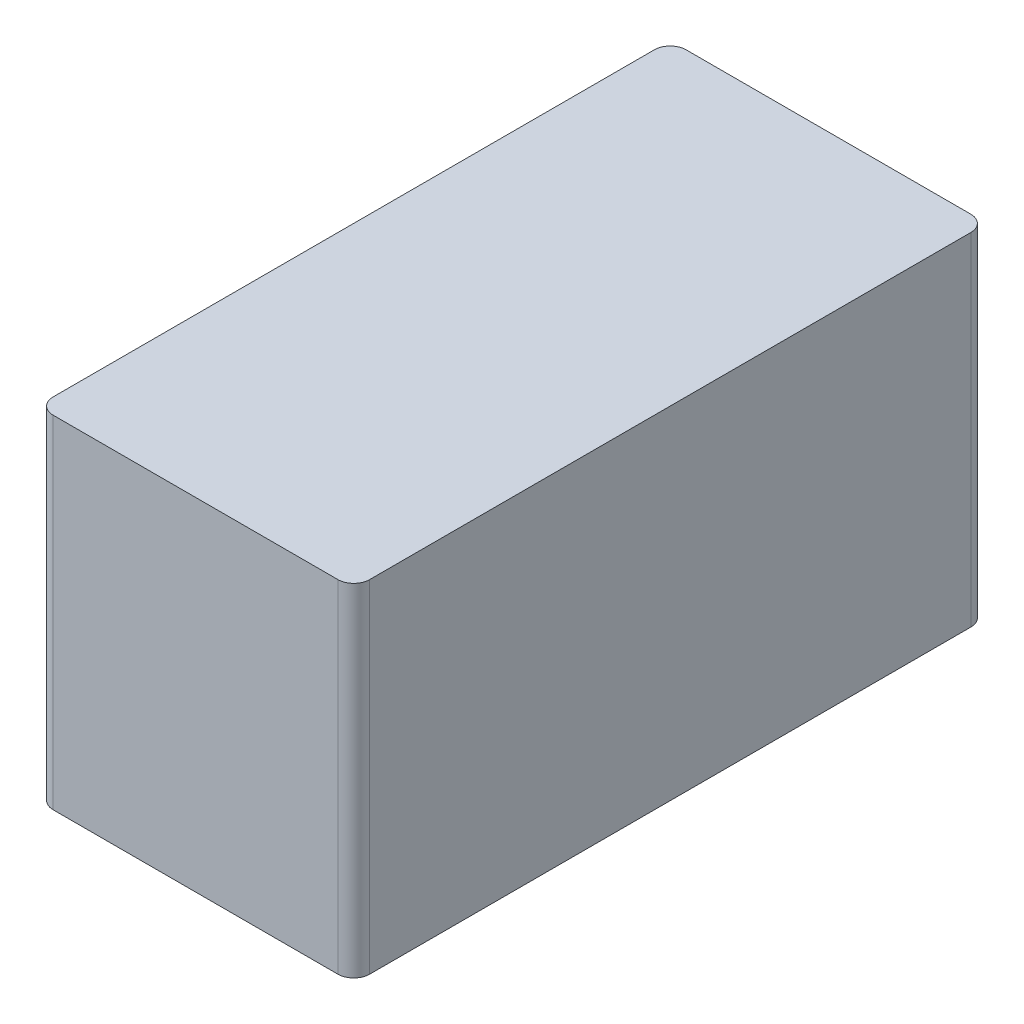
SolidWorks part; units mm, degrees
material "Polyethylene Cross-Linked"
ref_plane "Front Plane" through (0, 0, 0) normal (0, 0, 1) x (1, 0, 0)
ref_plane "Top Plane" through (0, 0, 0) normal (0, 1, 0) x (1, 0, 0)
ref_plane "Right Plane" through (0, 0, 0) normal (1, 0, 0) x (0, 0, -1)
sketch "Sketch1" plane through (0, 0, 0) normal (0, 1, 0) x (1, 0, 0)
  line L1 (-10, 20) -> (10, 20)
  line L2 (-10, 20) -> (-10, -20)
  line L3 (-10, -20) -> (10, -20)
  line L4 (10, 20) -> (10, -20)
  line L5 (-10, 20) -> (10, -20) construction
  line L6 (-10, -20) -> (10, 20) construction
  point P0 (0, 0)
  dimension "D1" = 20
  dimension "D2" = 40
extrude "Boss-Extrude1" add sketch "Sketch1" along normal mid plane 21.6
fillet "Fillet1" radius 1 4 edges at (-10, 0, -20) (10, 0, -20) (10, 0, 20) (-10, 0, 20)
